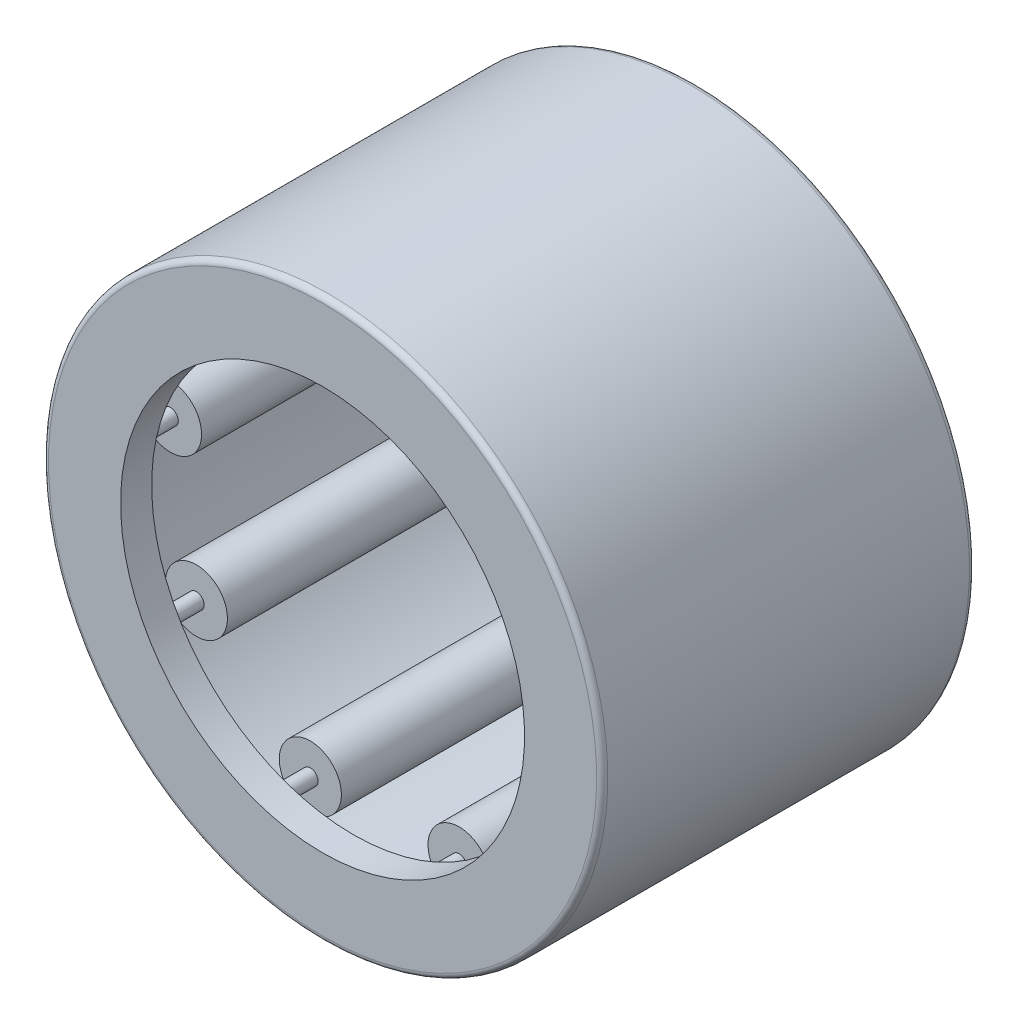
SolidWorks part; units mm, degrees
material "AISI 1020"
ref_plane "Front Plane" through (0, 0, 0) normal (0, 0, 1) x (1, 0, 0)
ref_plane "Top Plane" through (0, 0, 0) normal (0, 1, 0) x (1, 0, 0)
ref_plane "Right Plane" through (0, 0, 0) normal (1, 0, 0) x (0, 0, -1)
sketch "Sketch1" plane through (0, 0, 0) normal (1, 0, 0) x (0, 0, -1)
  line L0 (-4, 0) -> (4, 0) construction
  line L1 (0, 0) -> (0, 6) construction
  line L2 (-4, 0) -> (-4, 6) construction
  line L3 (-4, 6) -> (4, 6)
  line L4 (4, 6) -> (4, 0) construction
  line L5 (4, 0) -> (3.3333, 0) construction
  line L6 (3.3333, 0) -> (3.3333, 5.3333) construction
  line L7 (3.3333, 5.3333) -> (-3.3333, 5.3333)
  line L8 (-3.3333, 5.3333) -> (-3.3333, 0) construction
  line L9 (-3.3333, 0) -> (-4, 0) construction
  line L10 (-4, 6) -> (-4, 4.3333)
  line L11 (-4, 4.3333) -> (-3.3333, 4.3333)
  line L12 (-3.3333, 4.3333) -> (-3.3333, 5.3333)
  line L13 (3.3333, 6) -> (3.3333, 5.3333) construction
  line L14 (3.3333, 5.3333) -> (3.3333, 4.3333)
  line L15 (3.3333, 4.3333) -> (4, 4.3333)
  line L16 (4, 4.3333) -> (4, 6)
  line L17 (3.3333, 5.3333) -> (3.3333, 4.6667) construction
  line L18 (3.3333, 4.6667) -> (3.3333, 4) construction
  line L19 (3.3333, -5.3333) -> (3.3333, -4.6667) construction
  line L20 (3.3333, -6) -> (3.3333, -5.3333) construction
  line L21 (4, -4.3333) -> (4, -6) construction
  line L22 (3.3333, -4.3333) -> (4, -4.3333) construction
  line L23 (3.3333, -5.3333) -> (3.3333, -4.3333) construction
  line L24 (-3.3333, -4.3333) -> (-3.3333, -5.3333) construction
  line L25 (-4, -4.3333) -> (-3.3333, -4.3333) construction
  line L26 (-4, -6) -> (-4, -4.3333) construction
  line L27 (3.3333, -5.3333) -> (-3.3333, -5.3333) construction
  line L28 (-4, -6) -> (4, -6) construction
  point P5 (0, 4)
  dimension "Width" = 8
  dimension "OD" = 12
  dimension "Shaft Dia" = 8
revolve "Revolve1" add sketch "Sketch1" angle 360 about L0
sketch "Sketch2" plane through (0, 0, 0) normal (1, 0, 0) x (0, 0, -1)
  line L0 (3.3333, 5.3333) -> (-3.3333, 5.3333) construction
  line L1 (-2.6667, 4.6667) -> (2.6667, 4.6667) construction
  line L2 (-2.6667, 4.6667) -> (-2.6667, 5.3333) construction
  line L3 (-2.6667, 5.3333) -> (2.6667, 5.3333)
  line L4 (2.6667, 4.6667) -> (2.6667, 5.3333) construction
  line L5 (3.3333, 4.3333) -> (4, 4.3333) construction
  line L6 (-3.3333, 4.6667) -> (-2.6667, 4.6667) construction
  line L7 (2.6667, 4.6667) -> (3.3333, 4.6667) construction
  line L8 (-4, 4.3333) -> (-3.3333, 4.3333) construction
  line L9 (-2.6667, 4.8333) -> (-2.6667, 4.5) construction
  line L10 (-3.3333, 4.6667) -> (-3.3333, 4.3333) construction
  line L11 (-2.6667, 5.3333) -> (-2.6667, 4.8333)
  line L12 (2.6667, 5.3333) -> (2.6667, 4.8333)
  line L13 (2.6667, 4.8333) -> (-2.6667, 4.8333)
  line L14 (0, 5.3333) -> (0, 4) construction
  line L15 (-3.3333, 4.3333) -> (-3.3333, 5.3333) construction
  line L16 (-2.6667, 4.5) -> (-3.3333, 4.5) construction
  line L17 (0, 0) -> (4, 0) construction
  line L18 (-2.6667, -4.5) -> (-3.3333, -4.5) construction
  line L19 (0, -5.3333) -> (0, -4) construction
  line L20 (-3.3333, -4.6667) -> (-3.3333, -4.3333) construction
  line L21 (-2.6667, -4.8333) -> (-2.6667, -4.5) construction
  line L22 (2.6667, -4.6667) -> (3.3333, -4.6667) construction
  line L23 (-3.3333, -4.6667) -> (-2.6667, -4.6667) construction
  line L24 (2.6667, -4.6667) -> (2.6667, -5.3333) construction
  line L25 (-2.6667, -4.6667) -> (-2.6667, -5.3333) construction
  line L26 (-2.6667, -4.6667) -> (2.6667, -4.6667) construction
  line L27 (2.6667, -4.8333) -> (-2.6667, -4.8333) construction
  line L28 (2.6667, -5.3333) -> (2.6667, -4.8333) construction
  line L29 (-2.6667, -5.3333) -> (-2.6667, -4.8333) construction
  line L30 (-2.6667, -5.3333) -> (2.6667, -5.3333) construction
  line L31 (4, -6) -> (4, 6) construction
  line L32 (3.3333, 5.3333) -> (3.3333, 4.3333) construction
  point P16 (0, 4.6667)
revolve "Revolve2" add sketch "Sketch2" angle 360 about L1
sketch "Sketch3" plane through (0, 0, 0) normal (1, 0, 0) x (0, 0, -1)
  line L0 (3.3333, 5.3333) -> (3.3333, 4.3333) construction
  line L1 (-3.3333, 4.6667) -> (3.3333, 4.6667)
  line L2 (-3.3333, 4.6667) -> (-3.3333, 4.8333)
  line L3 (-3.3333, 4.8333) -> (3.3333, 4.8333)
  line L4 (3.3333, 4.6667) -> (3.3333, 4.8333)
  line L5 (0, 0) -> (4, 0) construction
  line L6 (4, -6) -> (4, 6) construction
  line L7 (3.3333, -4.6667) -> (3.3333, -4.8333) construction
  line L8 (-3.3333, -4.8333) -> (3.3333, -4.8333) construction
  line L9 (-3.3333, -4.6667) -> (-3.3333, -4.8333) construction
  line L10 (-3.3333, -4.6667) -> (3.3333, -4.6667) construction
revolve "Revolve3" add sketch "Sketch3" angle 360 about L1
ref_axis "Axis1" through (0, 0, -4) along (0, 0, 1)
pattern_circular "CirPattern1" count 9 every 40 about axis through (0, 0, -4) along (0, 0, 1) of bodies 166 167
fillet "Fillet1" radius 0.12 2 edges at (0, -6, -4) (0, -6, 4)
sketch "Sketch4" plane through (0, 0, 0) normal (1, 0, 0) x (0, 0, -1)
  line L0 (2.6667, 5.3333) -> (2.6667, 4.8333) construction
  line L1 (3.88, 4) -> (2.6667, 4)
  line L2 (3.88, 4) -> (3.88, 4.3333)
  line L3 (3.88, 4.3333) -> (2.6667, 4.3333)
  line L4 (2.6667, 4) -> (2.6667, 4.3333)
  line L5 (-4, 4.3333) -> (-3.3333, 4.3333) construction
  line L6 (3.88, -6) -> (3.88, 6) construction
revolve "Revolve4" [suppressed] add sketch "Sketch4" angle 360 about L0
sketch "Sketch5" plane through (0, 0, 0) normal (1, 0, 0) x (0, 0, -1)
  line L0 (-3.88, 6) -> (-3.88, -6) construction
  line L1 (-2.6667, 4) -> (-3.88, 4)
  line L2 (-2.6667, 4) -> (-2.6667, 4.3333)
  line L3 (-2.6667, 4.3333) -> (-3.88, 4.3333)
  line L4 (-3.88, 4) -> (-3.88, 4.3333)
  line L5 (-2.6667, 5.3333) -> (-2.6667, 4.8333) construction
revolve "Revolve5" [suppressed] add sketch "Sketch5" angle 360 about L0
equation "\"Angle@CirPattern1\" = 360/\"Rollers@CirPattern1\""
equation "\"Rollers@CirPattern1\" = \"OD@Sketch1\"*.75"
equation "\"D1@Fillet1\" = \"OD@Sketch1\"*.01"
